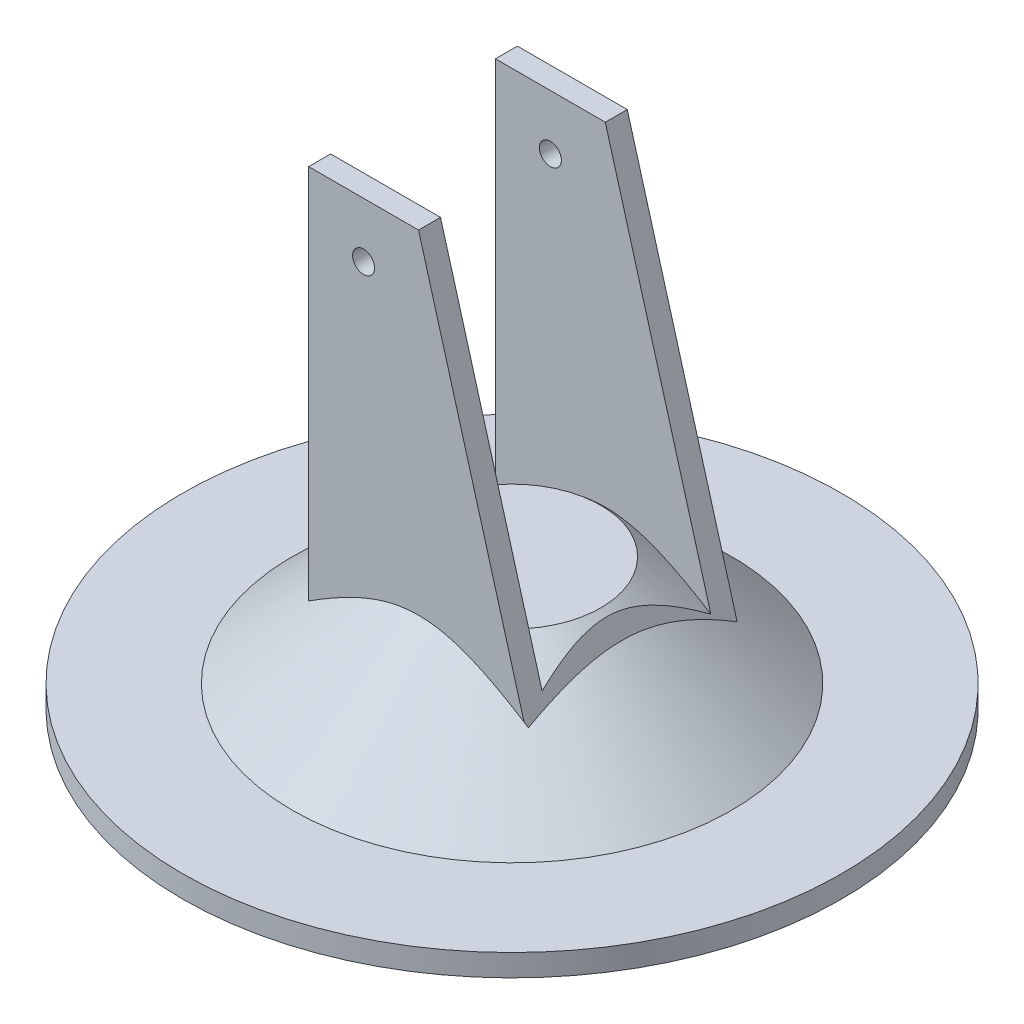
SolidWorks part; units mm, degrees
ref_plane "Front Plane" through (0, 0, 0) normal (0, 0, 1) x (1, 0, 0)
ref_plane "Top Plane" through (0, 0, 0) normal (0, 1, 0) x (1, 0, 0)
ref_plane "Right Plane" through (0, 0, 0) normal (1, 0, 0) x (0, 0, -1)
sketch "Sketch1" plane through (0, 0, 0) normal (0, 1, 0) x (1, 0, 0)
  circle A0 centre (0, -0.986) radius 30
  dimension "D1" = 60
extrude "Boss-Extrude1" add sketch "Sketch1" along normal blind 2
sketch "Sketch2" plane through (0, 2, 0) normal (0, 1, 0) x (1, 0, 0)
  circle A2 centre (0, -0.986) radius 20
  circle A3 centre (0, -0.986) radius 20
  dimension "D1" = 10
extrude "Boss-Extrude2" add sketch "Sketch2" along normal blind 10 draft 50
sketch "Sketch3" plane through (0, 2, 0) normal (0, 1, 0) x (1, 0, 0)
  line L1 (-10, -9.5) -> (10, -9.5)
  line L2 (-10, -9.5) -> (-10, 9.5)
  line L3 (-10, 9.5) -> (10, 9.5)
  line L4 (10, -9.5) -> (10, 9.5)
  line L5 (-10, -9.5) -> (10, 9.5) construction
  line L6 (-10, 9.5) -> (10, -9.5) construction
  line L7 (10, 9.5) -> (-10, 9.5)
  line L8 (10, 9.5) -> (10, 7.5)
  line L9 (10, 7.5) -> (-10, 7.5)
  line L10 (-10, 9.5) -> (-10, 7.5)
  line L11 (10, -9.5) -> (-10, -9.5)
  line L12 (10, -9.5) -> (10, -7.5)
  line L13 (10, -7.5) -> (-10, -7.5)
  line L14 (-10, -9.5) -> (-10, -7.5)
  point P0 (0, 0)
  dimension "D1" = 19
  dimension "D2" = 20
  dimension "D3" = 2
  dimension "D4" = 2
extrude "Boss-Extrude3" add sketch "Sketch3" along normal blind 40 contours L9 L4 L3 L2 | L4 L13 L2 L1
sketch "Sketch5" plane through (0, 0, -9.5) normal (0, 0, -1) x (-1, 0, 0)
  line L0 (0, 42) -> (-10, 6.6235)
  line L1 (10, 42) -> (-10, 42) construction
  line L2 (-10, 6.6235) -> (-10, 42)
  line L3 (-10, 42) -> (0, 42)
extrude "Cut-Extrude1" cut sketch "Sketch5" against normal up to surface (19 mm away) up to face at (-0.4375, 25.8126, 9.5)
sketch "Sketch7" plane through (0, 0, -9.5) normal (0, 0, -1) x (-1, 0, 0)
  line L0 (10, 42) -> (0, 42) construction
  circle A0 centre (5, 37) radius 1
  point P4 (5, 42)
  dimension "D1" = 2
  dimension "D2" = 5
extrude "Cut-Extrude2" cut sketch "Sketch7" against normal up to surface (19 mm away) up to face at (-2.9865, 25.8436, 9.5)
sketch "Sketch8" plane through (0, 0, 0) normal (0, -1, 0) x (1, 0, 0)
  circle A2 centre (0, 0.986) radius 25
  circle A3 centre (0, 0.986) radius 25
  dimension "D1" = 5
extrude "Cut-Extrude3" cut sketch "Sketch8" against normal blind 2 draft 84
